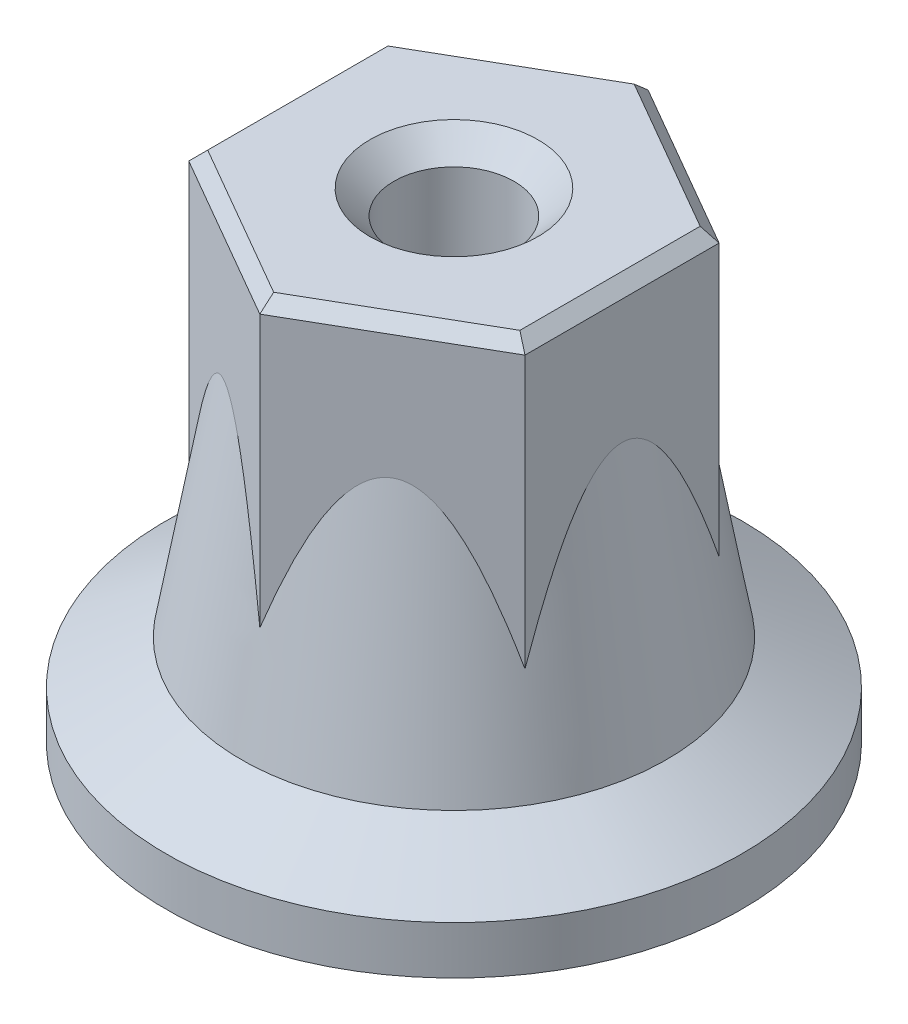
SolidWorks part; units mm, degrees
ref_plane "Front Plane" through (0, 0, 0) normal (0, 0, 1) x (1, 0, 0)
ref_plane "Top Plane" through (0, 0, 0) normal (0, 1, 0) x (1, 0, 0)
ref_plane "Right Plane" through (0, 0, 0) normal (1, 0, 0) x (0, 0, -1)
sketch "Sketch1" plane through (0, 0, 0) normal (0, 0, 1) x (1, 0, 0)
  line L0 (2.5, 15.518) -> (6, 15.518)
  line L1 (6, 15.518) -> (8.8536, -0.6655)
  line L2 (8.8536, -0.6655) -> (12, -2.482)
  line L3 (12, -2.482) -> (12, -4.482)
  line L4 (12, -4.482) -> (11.1161, -4.482)
  line L5 (0, -4.482) -> (0, 0)
  line L6 (0, 0) -> (2.5, 0)
  line L7 (2.5, 0) -> (2.5, 15.518)
  line L8 (1.7058, -4.482) -> (2.3965, -3.8791)
  line L9 (2.3965, -3.8791) -> (3.3354, -4.4875)
  line L10 (3.3354, -4.4875) -> (4.849, -4.4875)
  line L11 (4.849, -4.4875) -> (6.6783, -4.4875)
  line L12 (6.6783, -4.4875) -> (7.8306, -3.1537)
  line L13 (7.8306, -3.1537) -> (9.3747, -4.4875)
  line L14 (9.3747, -4.4875) -> (10.7183, -3.5662)
  line L15 (10.7183, -3.5662) -> (11.1161, -4.482)
  line L16 (1.7058, -4.482) -> (0, -4.482)
  dimension "D1" = 2.5
  dimension "D2" = 20
  dimension "D3" = 2
  dimension "D4" = 10
  dimension "D5" = 60
  dimension "D6" = 6
  dimension "D7" = 12
revolve "Revolve1" add sketch "Sketch1" angle 360 about L5
chamfer "Chamfer1" distance 1 angle 45 1 edges at (0, 15.518, -2.5)
sketch "Sketch2" plane through (0, 15.518, 0) normal (0, 1, 0) x (1, 0, 0)
  line L1 (0, 8.0829) -> (-7, 4.0415)
  line L2 (-7, 4.0415) -> (-7, -4.0415)
  line L3 (-7, -4.0415) -> (0, -8.0829)
  line L4 (0, -8.0829) -> (7, -4.0415)
  line L5 (7, -4.0415) -> (7, 4.0415)
  line L6 (7, 4.0415) -> (0, 8.0829)
  circle A0 centre (0, 0) radius 7 construction
  circle A2 centre (0, 0) radius 6
  circle A3 centre (0, 0) radius 6
  dimension "D1" = 14
  dimension "D2" = 0
extrude "Boss-Extrude1" add sketch "Sketch2" against normal blind 15
chamfer "Chamfer2" distance 0.5 angle 45 6 edges at (3.5, 15.518, -6.0622) (7, 15.518, 0) (3.5, 15.518, 6.0622) (-3.5, 15.518, 6.0622) (-7, 15.518, 0) (-3.5, 15.518, -6.0622)
hole_wizard "Ø5.0mm Dowel Hole1" positions "Sketch3" profile "Sketch4" hole size "Ø5.0" standard "ANSI Metric" end condition through all
sketch "Sketch3" plane through (0, -4.482, 0) normal (0, -1, 0) x (-1, 0, 0)
  point P0 (0, 0)
sketch "Sketch4" plane through (0, -4.482, 0) normal (1, 0, 0) x (0, 0, -1)
  line L0 (0, 0) -> (0, 20)
  line L1 (0, 20) -> (2.5, 20)
  line L2 (2.5, 20) -> (2.5, 0)
  line L5 (2.5, 0) -> (0, 0)
  line L11 (0, -6.35) -> (0, 107.95) construction
  dimension "Thru Hole Dia." = 5
  dimension "Thru Hole Depth" = 20
